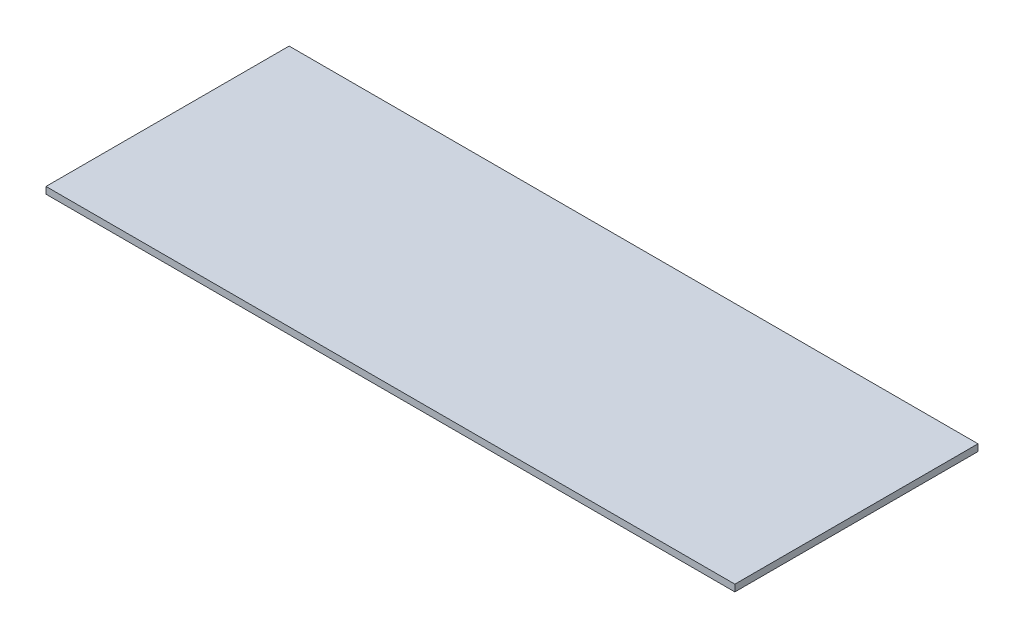
SolidWorks part; units mm, degrees
ref_plane "Front Plane" through (0, 0, 0) normal (0, 0, 1) x (1, 0, 0)
ref_plane "Top Plane" through (0, 0, 0) normal (0, 1, 0) x (1, 0, 0)
ref_plane "Right Plane" through (0, 0, 0) normal (1, 0, 0) x (0, 0, -1)
sketch "Sketch1" plane through (0, 0, 0) normal (0, 1, 0) x (1, 0, 0)
  line L1 (-323.85, -114.3) -> (323.85, -114.3)
  line L2 (-323.85, -114.3) -> (-323.85, 114.3)
  line L3 (-323.85, 114.3) -> (323.85, 114.3)
  line L4 (323.85, -114.3) -> (323.85, 114.3)
  line L5 (-323.85, -114.3) -> (323.85, 114.3) construction
  line L6 (-323.85, 114.3) -> (323.85, -114.3) construction
  point P0 (0, 0)
  dimension "D1" = 647.7
  dimension "D2" = 228.6
extrude "Boss-Extrude1" add sketch "Sketch1" along normal blind 6.35
